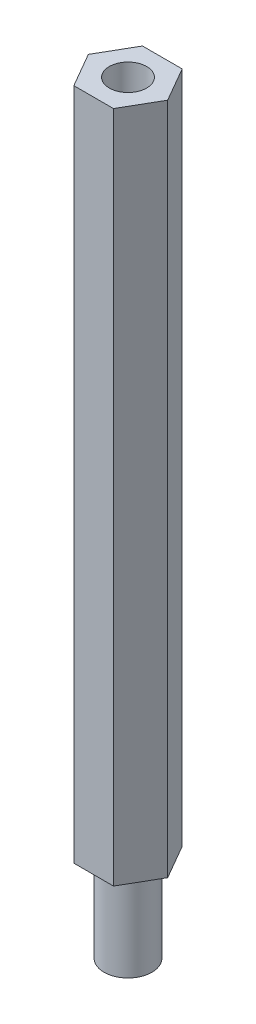
SolidWorks part; units mm, degrees
ref_plane "前视基准面" through (0, 0, 0) normal (0, 0, 1) x (1, 0, 0)
ref_plane "上视基准面" through (0, 0, 0) normal (0, 1, 0) x (1, 0, 0)
ref_plane "右视基准面" through (0, 0, 0) normal (1, 0, 0) x (0, 0, -1)
sketch "草图4" plane through (0, 0, 0) normal (0, 1, 0) x (1, 0, 0)
  line L0 (-12.7945, 0) -> (16.3015, 0) construction
  line L2 (1.325, -2.295) -> (2.65, 0)
  line L3 (2.65, 0) -> (1.325, 2.295)
  line L4 (1.325, 2.295) -> (-1.325, 2.295)
  line L5 (-1.325, 2.295) -> (-2.65, 0)
  line L6 (-2.65, 0) -> (-1.325, -2.295)
  line L7 (-1.325, -2.295) -> (1.325, -2.295)
  circle A0 centre (0, 0) radius 2.295 construction
  dimension "D1" = 5.3
extrude "凸台-拉伸1" add sketch "草图4" along normal blind 45
sketch "草图6" plane through (0, 0, 0) normal (0, -1, 0) x (-1, 0, 0)
  circle A0 centre (0, 0) radius 1.6
  dimension "D1" = 3.2
extrude "凸台-拉伸2" add sketch "草图6" along normal blind 6
cosmetic thread "装饰螺纹线1" parameters "D2"=2.5
sketch "草图7" plane through (0, 45, 0) normal (0, 1, 0) x (1, 0, 0)
  circle A0 centre (0, 0) radius 1.25
  dimension "D1" = 2.5
extrude "切除-拉伸1" cut sketch "草图7" against normal blind 5
cosmetic thread "装饰螺纹线2" parameters "D2"=3
